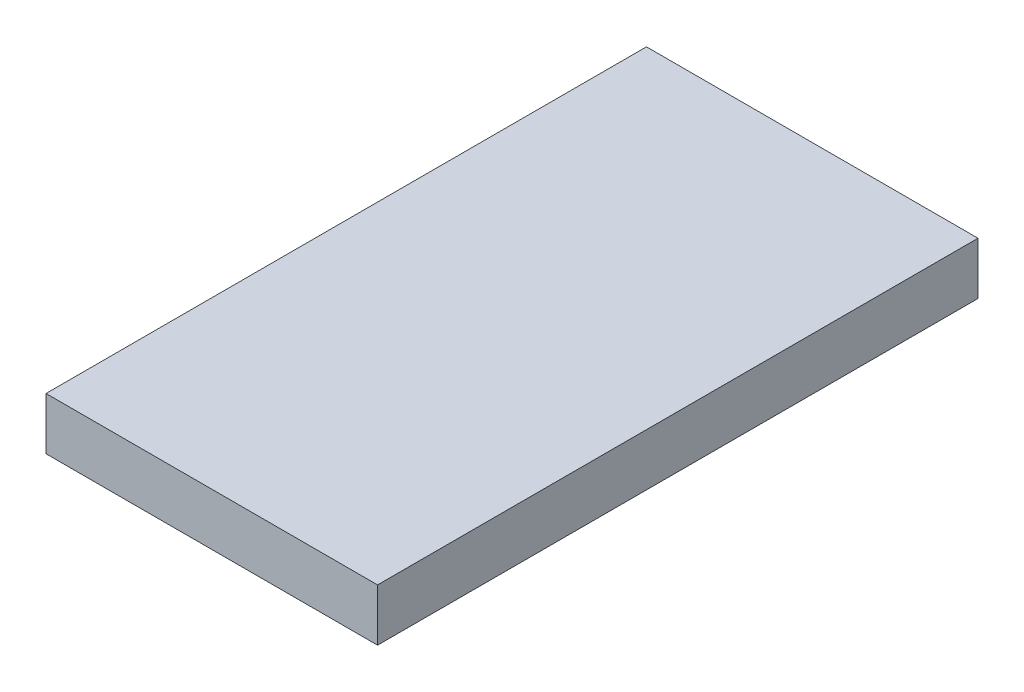
SolidWorks part; units mm, degrees
ref_plane "前视基准面" through (0, 0, 0) normal (0, 0, 1) x (1, 0, 0)
ref_plane "上视基准面" through (0, 0, 0) normal (0, 1, 0) x (1, 0, 0)
ref_plane "右视基准面" through (0, 0, 0) normal (1, 0, 0) x (0, 0, -1)
other "Configuration Table"
sketch "草图1" plane through (0, 0, 0) normal (0, 1, 0) x (1, 0, 0)
  line L1 (0, 0) -> (12.7, 0)
  line L2 (0, 0) -> (0, -23)
  line L3 (0, -23) -> (12.7, -23)
  line L4 (12.7, 0) -> (12.7, -23)
  dimension "D1" = 12.7
  dimension "D2" = 23
extrude "凸台-拉伸1" add sketch "草图1" along normal blind 2
